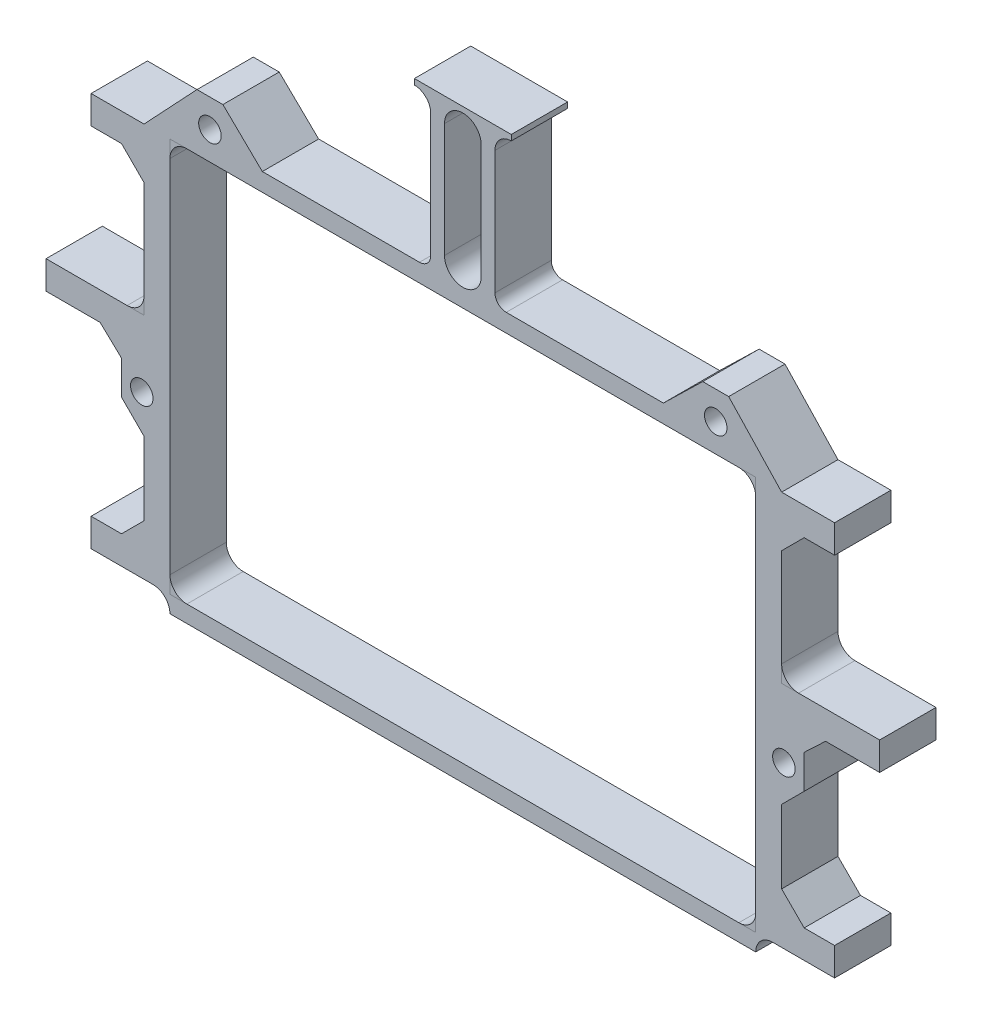
SolidWorks part; units mm, degrees
ref_plane "Alzado" through (0, 0, 0) normal (0, 0, 1) x (1, 0, 0)
ref_plane "Planta" through (0, 0, 0) normal (0, 1, 0) x (1, 0, 0)
ref_plane "Vista lateral" through (0, 0, 0) normal (1, 0, 0) x (0, 0, -1)
sketch "Croquis1" plane through (0, 0, 0) normal (0, 0, 1) x (1, 0, 0)
  line L1 (-37, -26) -> (37, -26)
  line L2 (-37, -26) -> (-37, 26)
  line L3 (-37, 26) -> (37, 26)
  line L4 (37, -26) -> (37, 26)
  line L5 (-37, -26) -> (37, 26) construction
  line L6 (-37, 26) -> (37, -26) construction
  point P0 (0, 0)
extrude "Saliente-Extruir1" add sketch "Croquis1" along normal blind 5
sketch "Croquis2" plane through (0, 0, 5) normal (0, 0, 1) x (1, 0, 0)
  line L0 (0, 26) -> (0, -26) construction
  line L1 (37, 26) -> (-37, 26) construction
  line L2 (-37, -26) -> (37, -26) construction
  line L3 (-26, -24.5) -> (26, -24.5)
  line L4 (-26, 10.5) -> (26, 10.5)
  line L5 (-26, 10.5) -> (-26, -24.5)
  line L6 (26, -24.5) -> (26, 10.5)
  point P9 (0, -24.5)
  point P12 (0, 10.5)
  dimension "D1" = 1.5
  dimension "D2" = 35
  dimension "D3" = 52
  dimension "D4" = 52
extrude "Cortar-Extruir1" cut sketch "Croquis2" against normal blind 5
sketch "Croquis3" plane through (0, 0, 5) normal (0, 0, 1) x (1, 0, 0)
  line L0 (26, -24.5) -> (33, -24.5) construction
  line L1 (33, -24.5) -> (33, -22)
  line L2 (28.3, -26) -> (28.3, 26) construction
  line L3 (-37, -26) -> (37, -26) construction
  line L4 (37, 26) -> (-37, 26) construction
  line L5 (26, -24.5) -> (26, 10.5) construction
  line L6 (26, -24.5) -> (26, -26) construction
  line L7 (33, -24.5) -> (27.5, -24.5)
  line L8 (33, -22) -> (30.3, -22)
  line L9 (30.3, -22) -> (28.3, -20)
  line L10 (28.3, -20) -> (28.3, -13.5)
  line L11 (28.3, -13.5) -> (30.3, -11.5)
  line L12 (30.3, -11.5) -> (30.3, -8.5)
  line L13 (30.3, -8.5) -> (32.2, -6.7)
  line L14 (32.2, -6.7) -> (37, -6.7)
  line L15 (37, -26) -> (37, 26) construction
  line L16 (37, -6.7) -> (37, -4.2)
  line L17 (37, -4.2) -> (28.3, -4.2)
  line L18 (26, 10.5) -> (33, 10.5) construction
  line L19 (33, 10.5) -> (33, 8)
  line L20 (33, 8) -> (30.3, 8)
  line L21 (30.3, 8) -> (28.3, 6)
  line L22 (28.3, 6) -> (28.3, -4.2)
  line L23 (28.3, 10.5) -> (23.6, 15.5)
  line L24 (26, 10.5) -> (-26, 10.5) construction
  line L25 (33, 10.5) -> (28.3, 10.5)
  line L26 (23.6, 15.5) -> (21.3, 15.5)
  line L27 (0, 12.1) -> (43.3575, 12.1) construction
  line L28 (21.3, 15.5) -> (17.8, 12.1)
  line L29 (0, 26) -> (0, 10.5) construction
  line L30 (2.85, 26) -> (2.85, 12.1)
  line L31 (1.63, 26) -> (1.63, 12.1)
  line L32 (2.85, 12.1) -> (17.8, 12.1)
  line L33 (0, 26) -> (4.3, 26)
  line L34 (4.3, 26) -> (4.3, 25.5)
  line L35 (4.3, 25.5) -> (2.85, 25.5) construction
  line L36 (1.63, 25.5) -> (0, 25.5) construction
  line L37 (0, 25.5) -> (0, 26)
  line L38 (0, 12.1) -> (0, 10.5)
  line L39 (0, 10.5) -> (26, 10.5)
  line L40 (26, 10.5) -> (26, -24.5)
  line L41 (26, -24.5) -> (26, -26)
  line L43 (0, 22.24) -> (0, 15.36)
  line L44 (4.3, 26) -> (37, 26)
  line L45 (37, 26) -> (37, -26)
  line L46 (37, -26) -> (29, -26)
  circle A1 centre (28.5, -10.2) radius 1
  circle A2 centre (3.85, 13.1) radius 1
  circle A3 centre (0, 13.73) radius 1.63
  circle A5 centre (4.3, 24.05) radius 1.45
  circle A6 centre (0, 23.87) radius 1.63
  circle A7 centre (27.5, -26) radius 1.5
  circle A8 centre (22.45, 13) radius 1
  line M19 (37, -26) -> (37, 26)
  line M20 (37, 26) -> (-37, 26)
  line M22 (-37, -26) -> (37, -26)
  dimension "D4" = 2
  dimension "D17" = 2.5
  dimension "D18" = 14.3
  dimension "D26" = 2
  dimension "D27" = 2
  dimension "D28" = 2
  dimension "D32" = 2.5
  dimension "D1" = 7
  dimension "D2" = 2.5
  dimension "D3" = 2.3
  dimension "D5" = 2
  dimension "D6" = 6.5
  dimension "D7" = 2
  dimension "D8" = 2
  dimension "D9" = 2.5
  dimension "D10" = 17.8
  dimension "D11" = 4.8
  dimension "D12" = 3
  dimension "D13" = 7
  dimension "D14" = 12.2
  dimension "D15" = 2
  dimension "D16" = 2
  dimension "D19" = 5
  dimension "D20" = 9.4
  dimension "D21" = 2.3
  dimension "D22" = 1.6
  dimension "D23" = 3.5
  dimension "D24" = 2.85
  dimension "D25" = 1.22
  dimension "D29" = 4.3
  dimension "D30" = 0.5
  dimension "D31" = 0.5
extrude "Cortar-Extruir2" cut sketch "Croquis3" against normal blind 5 contours A7 L14 L13 L12 L11 L10 L9 L8 L1 L7 M22 M19 | A7 M22 | A5 L30 A2 L32 L28 L26 L23 L25 L19 L20 L21 L22 L17 L34 M19 M20 | A2 | A5 | A6 L43 A3 L31 | A6 | A3 | A8 | A1
mirror "Simetría2" about plane through (0, 0, 0) normal (-1, 0, 0) of "Cortar-Extruir2"
sketch "Croquis4" plane through (0, 0, 5) normal (0, 0, 1) x (1, 0, 0)
  line L0 (28.3, -4.2) -> (28.3, -2.7)
  line L1 (26, 10.5) -> (-26, 10.5)
  line L2 (26, 10.5) -> (26, -24.5)
  line L3 (26, -24.5) -> (-26, -24.5)
  line L4 (-26, 10.5) -> (-26, -24.5)
  line L5 (28.3, 6) -> (28.3, -4.2) construction
  line L6 (28.3, -4.2) -> (29.8, -4.2)
  line L7 (37, -4.2) -> (28.3, -4.2) construction
  line L8 (-28.3, -4.2) -> (-29.8, -4.2)
  line L9 (-37, -4.2) -> (-28.3, -4.2) construction
  line L10 (-28.3, -4.2) -> (-28.3, -2.7)
  line L11 (-28.3, 6) -> (-28.3, -4.2) construction
  circle A4 centre (-24.5, 9) radius 1.5
  circle A5 centre (24.5, 9) radius 1.5
  circle A6 centre (24.5, -23) radius 1.5
  circle A7 centre (-24.5, -23) radius 1.5
  circle A10 centre (29.8, -2.7) radius 1.5
  circle A11 centre (-29.8, -2.7) radius 1.5
  dimension "D1" = 3
  dimension "D2" = 3
  dimension "D3" = 3
  dimension "D4" = 3
  dimension "D5" = 1.5
  dimension "D6" = 1.5
  dimension "D7" = 1.5
  dimension "D8" = 1.5
extrude "Saliente-Extruir2" add sketch "Croquis4" against normal blind 5 separate body contours A4 L1 L4 | A11 L8 L10 | A7 L4 L3 | A6 L3 L2 | A10 L0 L6 | A5 L2 L1
